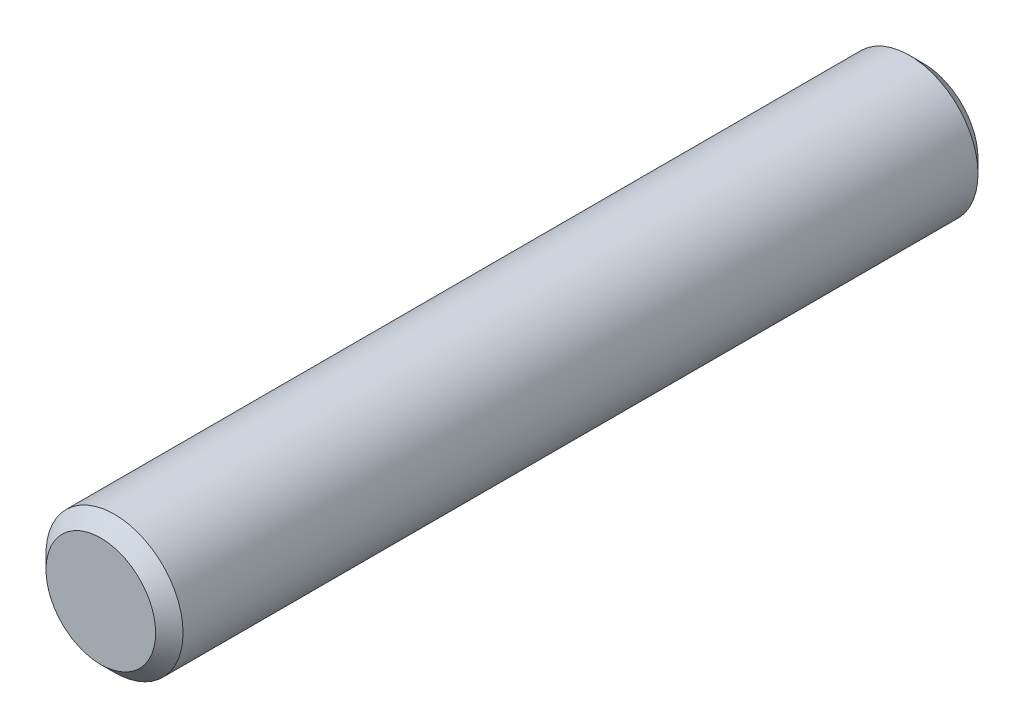
SolidWorks part; units mm, degrees
material "AISI 304"
ref_plane "前视基准面" through (0, 0, 0) normal (0, 0, 1) x (1, 0, 0)
ref_plane "上视基准面" through (0, 0, 0) normal (0, 1, 0) x (1, 0, 0)
ref_plane "右视基准面" through (0, 0, 0) normal (1, 0, 0) x (0, 0, -1)
sketch "草图1" plane through (0, 0, 0) normal (0, 0, 1) x (1, 0, 0)
  circle A0 centre (0, 0) radius 2.5
  dimension "D1" = 5
extrude "凸台-拉伸1" add sketch "草图1" along normal mid plane 30
chamfer "倒角1" distance 0.5 angle 45 2 edges at (2.5, 0, -15) (2.5, 0, 15)
